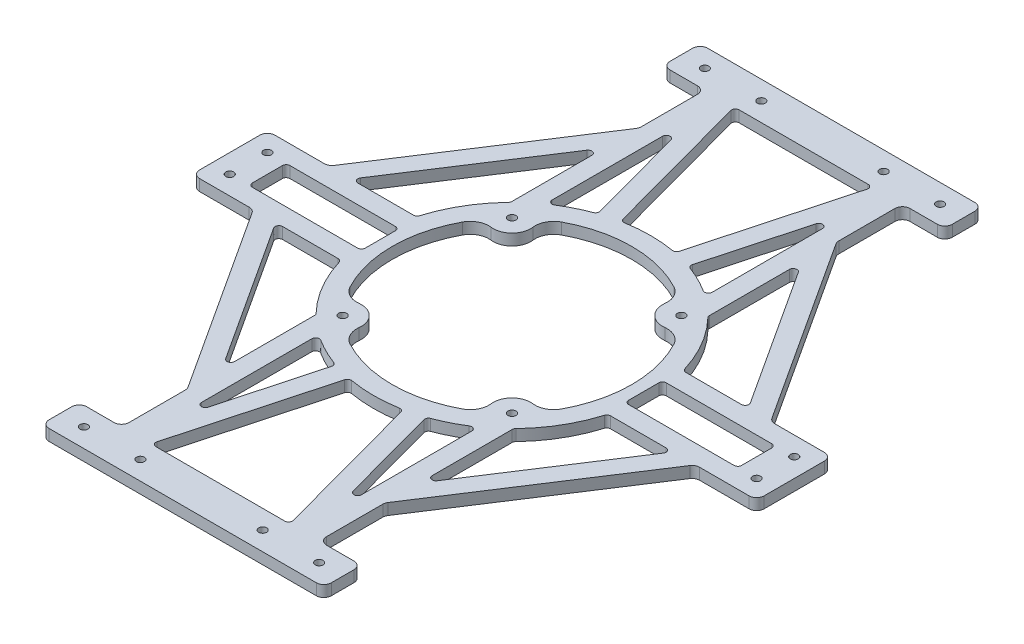
SolidWorks part; units mm, degrees
material "环氧树脂FR-4"
ref_plane "前视基准面" through (0, 0, 0) normal (0, 0, 1) x (1, 0, 0)
ref_plane "上视基准面" through (0, 0, 0) normal (0, 1, 0) x (1, 0, 0)
ref_plane "右视基准面" through (0, 0, 0) normal (1, 0, 0) x (0, 0, -1)
sketch "草图15" plane through (0, 0, 0) normal (0, 1, 0) x (1, 0, 0)
  line L1 (-45, 45) -> (45, 45) construction
  line L2 (-45, 45) -> (-45, -45) construction
  line L3 (-45, -45) -> (45, -45) construction
  line L4 (45, 45) -> (45, -45) construction
  line L5 (-45, 45) -> (45, -45) construction
  line L6 (-45, -45) -> (45, 45) construction
  arc A8 (-51.4937, 37.3952) -> (-51.4937, -37.3952) centre (0, 0) ccw
  arc A11 (-51.4937, 37.3952) -> (-37.3952, 51.4937) centre (-45, 45) ccw
  arc A12 (37.3952, 51.4937) -> (51.4937, 37.3952) centre (45, 45) ccw
  arc A13 (51.4937, -37.3952) -> (37.3952, -51.4937) centre (45, -45) ccw
  arc A14 (-37.3952, -51.4937) -> (-51.4937, -37.3952) centre (-45, -45) ccw
  arc A15 (-37.3952, -51.4937) -> (37.3952, -51.4937) centre (0, 0) ccw
  arc A16 (51.4937, -37.3952) -> (51.4937, 37.3952) centre (0, 0) ccw
  arc A17 (37.3952, 51.4937) -> (-37.3952, 51.4937) centre (0, 0) ccw
  point P0 (0, 0)
  point P13 (60.8589, 18.6064)
  dimension "D3" = 20
  dimension "D4" = 4
  dimension "D1" = 90
  dimension "D2" = 90
sketch "草图17" plane through (0, 0, 0) normal (0, 1, 0) x (1, 0, 0)
  line L0 (-45, 45) -> (45, -45) construction
  line L1 (-47.5, 175) -> (47.5, 175) construction
  line L2 (-47.5, 175) -> (-47.5, -175) construction
  line L3 (-47.5, -175) -> (47.5, -175) construction
  line L4 (47.5, 175) -> (47.5, -175) construction
  line L5 (-47.5, 175) -> (47.5, -175) construction
  line L6 (-47.5, -175) -> (47.5, 175) construction
  point P0 (0, 0)
  dimension "D1" = 95
  dimension "D2" = 350
  dimension "D3" = 47.5
sketch "草图18" plane through (0, 0, 0) normal (0, 1, 0) x (1, 0, 0)
  line L1 (-150, 20) -> (150, 20) construction
  line L2 (-150, 20) -> (-150, -20) construction
  line L3 (-150, -20) -> (150, -20) construction
  line L4 (150, 20) -> (150, -20) construction
  line L5 (-150, 20) -> (150, -20) construction
  line L6 (-150, -20) -> (150, 20) construction
  point P0 (0, 0)
  dimension "D1" = 40
  dimension "D2" = 300
sketch "草图19" plane through (0, 0, 0) normal (0, 1, 0) x (1, 0, 0)
  line L0 (-75, -175) -> (75, -175)
  line L9 (0, -55) -> (0, 55) construction
  line L10 (-52.5, 175) -> (-52.5, -175)
  line L11 (-52.5, -120) -> (-52.5, -155)
  line L12 (-150, 20) -> (-150, -20)
  line L13 (117.5, -20) -> (52.5, -120)
  line L14 (52.5, -120) -> (52.5, -155)
  line L15 (75, -155) -> (52.5, -155)
  line L16 (75, -155) -> (75, -175)
  line L17 (117.5, -20) -> (150, -20)
  line L18 (150, -20) -> (150, 20)
  line L19 (-55, 0) -> (55, 0) construction
  line L20 (117.5, 20) -> (150, 20)
  line L21 (-75, -155) -> (-52.5, -155)
  line L22 (-150, 20) -> (-117.5, 20)
  line L23 (-75, -155) -> (-75, -175)
  line L25 (117.5, 20) -> (52.5, 120)
  line L26 (-117.5, 20) -> (-52.5, 120)
  line L27 (-75, -155) -> (75, -155) construction
  line L28 (-150, -20) -> (-117.5, -20)
  line L29 (-52.5, 120) -> (-52.5, 155)
  line L30 (52.5, 120) -> (52.5, 155)
  line L31 (-117.5, -20) -> (-52.5, -120)
  line L32 (-150, -20) -> (150, -20) construction
  line L33 (75, 155) -> (75, 175)
  line L34 (75, 155) -> (52.5, 155)
  line L35 (-75, 155) -> (-52.5, 155)
  line L36 (-75, 155) -> (-75, 175)
  line L37 (-75, 175) -> (75, 175)
  point P7 (-75, -135)
  point P11 (75, -135)
  dimension "D5" = 20
  dimension "D6" = 75
  dimension "D2" = 100
  dimension "D3" = 65
  dimension "D4" = 175
  dimension "D1" = 5
extrude "凸台-拉伸5" add sketch "草图19" along normal blind 6
extrude "切除-拉伸5" cut sketch "草图15" along normal through all
sketch "草图21" plane through (0, 6, 0) normal (0, 1, 0) x (1, 0, 0)
  line L0 (-47.5, 175) -> (-47.5, -175) construction
  line L1 (-75, -175) -> (75, -175) construction
  line L2 (-47.5, -175) -> (47.5, -175) construction
  line L3 (0, -55) -> (0, 55) construction
  line L4 (-55, 0) -> (55, 0) construction
  line L5 (-150, 20) -> (-150, -20) construction
  point P0 (-62.5, -165)
  point P6 (-32.5, -165)
  point P10 (32.5, -165)
  point P11 (62.5, -165)
  point P14 (62.5, 165)
  point P15 (32.5, 165)
  point P16 (-32.5, 165)
  point P17 (-62.5, 165)
  point P18 (-140, 10)
  point P21 (-140, -10)
  point P22 (140, -10)
  point P24 (140, 10)
  dimension "D1" = 15
  dimension "D2" = 10
  dimension "D3" = 15
  dimension "D4" = 10
  dimension "D5" = 10
  dimension "D6" = 10
hole_wizard "Ø4.2 (4.2) 直径孔4" positions "3D草图4" profile "草图22" hole size "Ø4.2" standard "GB" end condition through all
sketch3d "3D草图4"
  point P0 (-62.5, 6, 165)
  point P3 (-32.5, 6, 165)
  point P6 (32.5, 6, 165)
  point P9 (62.5, 6, 165)
  point P12 (140, 6, -10)
  point P15 (140, 6, 10)
  point P18 (-140, 6, -10)
  point P21 (-140, 6, 10)
  point P24 (-62.5, 6, -165)
  point P27 (-32.5, 6, -165)
  point P30 (32.5, 6, -165)
  point P33 (62.5, 6, -165)
sketch "草图22" plane through (-62.5, 6, 165) normal (1, 0, 0) x (0, 0, 1)
  line L0 (0, 0) -> (0, 6)
  line L1 (0, 6) -> (2.1, 6)
  line L2 (2.1, 6) -> (2.1, 0)
  line L5 (2.1, 0) -> (0, 0)
  line L11 (0, -6.35) -> (0, 107.95) construction
  dimension "通孔孔直径" = 4.2
  dimension "通孔孔深度" = 6
sketch "草图23" plane through (0, 6, 0) normal (0, 1, 0) x (1, 0, 0)
  line L0 (36.8905, -155) -> (-36.8905, -155)
  line L1 (-55, 0) -> (55, 0) construction
  line L3 (150, -20) -> (150, 20) construction
  line L4 (117.5, -20) -> (150, -20) construction
  line L5 (14.42, -72.214) -> (36.8905, -155)
  line L8 (24.0708, -69.5944) -> (42.5, -137.4914)
  line L9 (42.5, 175) -> (42.5, -175)
  line L10 (42.5, 137.4914) -> (42.5, 60.1377)
  line L11 (-42.5, 60.1377) -> (-42.5, 137.4914)
  line L12 (-109.1156, -14.5501) -> (-44.1156, -114.5501)
  line L13 (-105.5731, -20) -> (-52.5, -101.651)
  line L14 (-42.5, -137.4914) -> (-24.0708, -69.5944)
  line L15 (44.1156, -114.5501) -> (109.1156, -14.5501)
  line L16 (52.5, -101.651) -> (105.5731, -20)
  line L17 (-36.8905, 155) -> (-14.42, 72.214)
  line L18 (-44.1156, 114.5501) -> (-109.1156, 14.5501)
  line L19 (-52.5, 101.651) -> (-105.5731, 20)
  line L20 (-42.5, 137.4914) -> (-24.0708, 69.5944)
  line L21 (24.0708, 69.5944) -> (42.5, 137.4914)
  line L22 (-36.8905, -155) -> (-14.42, -72.214)
  line L23 (14.42, 72.214) -> (36.8905, 155)
  line L24 (36.8905, 155) -> (-36.8905, 155)
  line L45 (109.1156, 14.5501) -> (44.1156, 114.5501)
  line L46 (105.5731, 20) -> (52.5, 101.651)
  line L48 (-52.5, 175) -> (-52.5, -175)
  line L49 (-52.5, 101.651) -> (-52.5, 51.6386)
  line L50 (-105.5731, -20) -> (-70.8717, -20)
  line L51 (52.5, 175) -> (52.5, -175)
  line L52 (52.5, 101.651) -> (52.5, 51.6386)
  line L53 (-150, -20) -> (150, -20) construction
  line L54 (105.5731, -20) -> (70.8717, -20)
  line L55 (-52.5, -51.6386) -> (-52.5, -101.651)
  line L56 (52.5, -51.6386) -> (52.5, -101.651)
  line L57 (-105.5731, 20) -> (-70.8717, 20)
  line L58 (70.8717, 20) -> (105.5731, 20)
  line L59 (-42.5, -60.1377) -> (-42.5, -137.4914)
  line L60 (42.5, -60.1377) -> (42.5, -137.4914)
  line L61 (-150, 20) -> (-150, -20) construction
  line L62 (-130, 10) -> (-70, 10)
  line L63 (-130, 10) -> (-130, -10)
  line L64 (-130, -10) -> (-70, -10)
  line L65 (-70, 10) -> (-70, -10)
  line L66 (-150, 20) -> (150, 20) construction
  line L67 (0, -55) -> (0, 55) construction
  line L68 (70, 10) -> (70, -10)
  line L69 (130, -10) -> (70, -10)
  line L70 (130, 10) -> (130, -10)
  line L71 (130, 10) -> (70, 10)
  arc A1 (-42.5, -60.1377) -> (-24.0708, -69.5944) centre (0, 0) ccw
  arc A2 (52.5, -51.6386) -> (70.8717, -20) centre (0, 0) ccw
  arc A3 (-52.5, 51.6386) -> (-70.8717, 20) centre (0, 0) ccw
  arc A4 (42.5, 60.1377) -> (24.0708, 69.5944) centre (0, 0) ccw
  arc A5 (70.8717, 20) -> (52.5, 51.6386) centre (0, 0) ccw
  arc A6 (-70.8717, -20) -> (-52.5, -51.6386) centre (0, 0) ccw
  arc A7 (-14.42, -72.214) -> (14.42, -72.214) centre (0, 0) ccw
  arc A8 (24.0708, -69.5944) -> (42.5, -60.1377) centre (0, 0) ccw
  arc A9 (-24.0708, 69.5944) -> (-42.5, 60.1377) centre (0, 0) ccw
  arc A10 (14.42, 72.214) -> (-14.42, 72.214) centre (0, 0) ccw
  dimension "D9" = 20
  dimension "D10" = 10
  dimension "D11" = 10
  dimension "D12" = 60
  dimension "D2" = 5
  dimension "D3" = 10
  dimension "D4" = 10
  dimension "D5" = 10
  dimension "D6" = 10
  dimension "D7" = 5
  dimension "D8" = 5
extrude "切除-拉伸6" cut sketch "草图23" against normal blind 10
sketch "草图24" plane through (0, 6, 0) normal (0, 1, 0) x (1, 0, 0)
  circle A0 centre (0, 0) radius 63.6396 construction
  point P10 (45, 45)
  point P11 (-45, 45)
  point P12 (45, -45)
  point P14 (-45, -45)
  dimension "D1" = 4
fillet "圆角2" radius 2 44 edges at (-130, 3, 10) (-130, 3, -10) (-70, 3, 10) (-70, 3, -10) (-52.5, 3, 51.6386) (-70.8717, 3, 20) (-105.5731, 3, 20) (-52.5, 3, 101.651) (-42.5, 3, 137.4914) (-24.0708, 3, 69.5944) (-42.5, 3, 60.1377) (-14.42, 3, 72.214) (14.42, 3, 72.214) (-36.8905, 3, 155) (36.8905, 3, 155) (42.5, 3, 137.4914) (24.0708, 3, 69.5944) (42.5, 3, 60.1377) (52.5, 3, 101.651) (105.5731, 3, 20) (70.8717, 3, 20) (52.5, 3, 51.6386) (130, 3, -10) (130, 3, 10) (70, 3, 10) (70, 3, -10) (105.5731, 3, -20) (70.8717, 3, -20) (52.5, 3, -51.6386) (52.5, 3, -101.651) (42.5, 3, -60.1377) (42.5, 3, -137.4914) (24.0708, 3, -69.5944) (14.42, 3, -72.214) (36.8905, 3, -155) (-36.8905, 3, -155) (-14.42, 3, -72.214) (-24.0708, 3, -69.5944) (-42.5, 3, -60.1377) (-42.5, 3, -137.4914) (-52.5, 3, -101.651) (-52.5, 3, -51.6386) (-70.8717, 3, -20) (-105.5731, 3, -20)
fillet "圆角3" radius 4 24 edges at (75, 3, -155) (52.5, 3, -155) (52.5, 3, -120) (-75, 3, -155) (-52.5, 3, -155) (-52.5, 3, -120) (-117.5, 3, -20) (-117.5, 3, 20) (117.5, 3, -20) (117.5, 3, 20) (52.5, 3, 120) (-52.5, 3, 120) (-52.5, 3, 155) (52.5, 3, 155) (75, 3, 155) (-75, 3, 155) (-150, 3, 20) (-150, 3, -20) (-75, 3, -175) (75, 3, -175) (150, 3, -20) (150, 3, 20) (75, 3, 175) (-75, 3, 175)
hole_wizard "Ø4.2 (4.2) 直径孔6" positions "3D草图6" profile "草图26" hole size "Ø4.2" standard "GB" end condition through all
sketch3d "3D草图6"
  point P0 (-45, 6, -45)
  point P3 (-45, 6, 45)
  point P6 (45, 6, 45)
  point P9 (45, 6, -45)
sketch "草图26" plane through (-45, 6, -45) normal (1, 0, 0) x (0, 0, 1)
  line L0 (0, 0) -> (0, 6)
  line L1 (0, 6) -> (2.1, 6)
  line L2 (2.1, 6) -> (2.1, 0)
  line L5 (2.1, 0) -> (0, 0)
  line L11 (0, -6.35) -> (0, 107.95) construction
  dimension "通孔孔直径" = 4.2
  dimension "通孔孔深度" = 6
fillet "圆角4" radius 10 8 edges at (-51.4937, 3, 37.3952) (-37.3952, 3, 51.4937) (37.3952, 3, 51.4937) (51.4937, 3, 37.3952) (51.4937, 3, -37.3952) (37.3952, 3, -51.4937) (-37.3952, 3, -51.4937) (-51.4937, 3, -37.3952)
